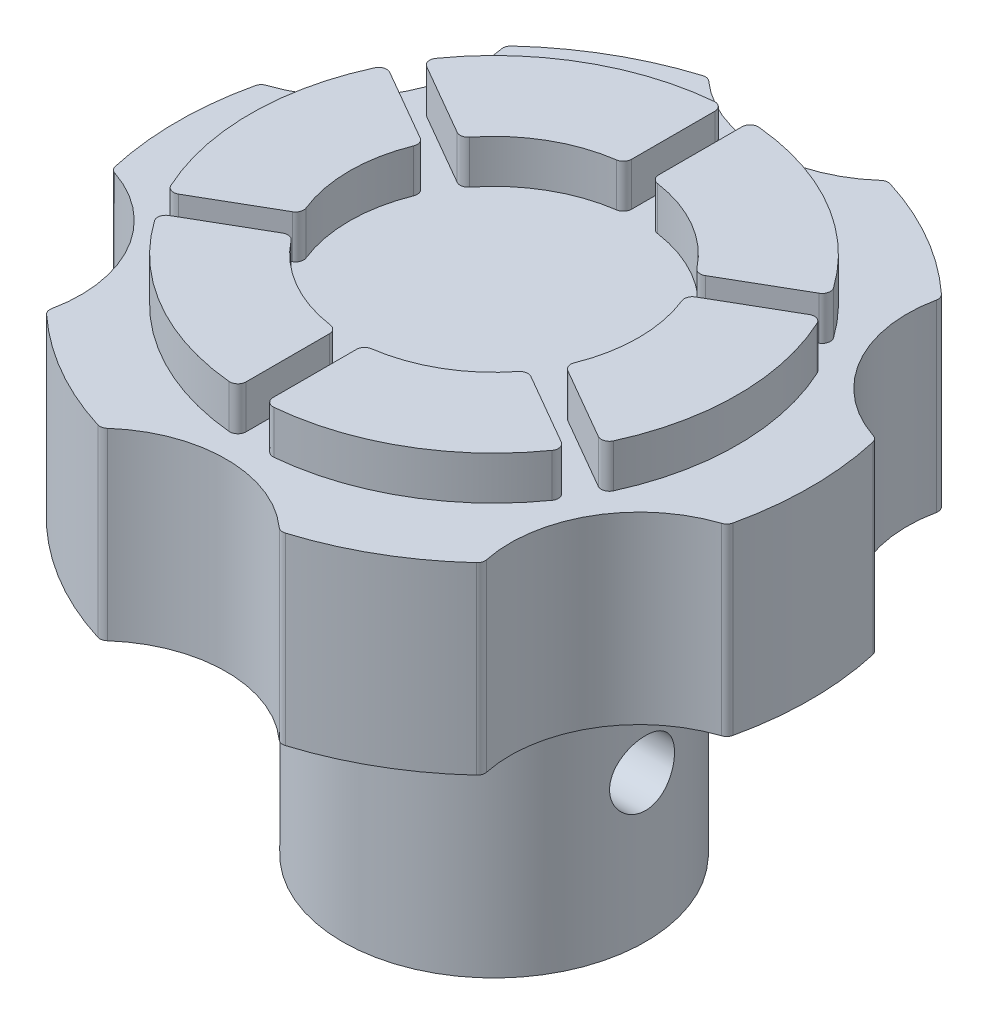
SolidWorks part; units mm, degrees
ref_plane "Alzado" through (0, 0, 0) normal (0, 0, 1) x (1, 0, 0)
ref_plane "Planta" through (0, 0, 0) normal (0, 1, 0) x (1, 0, 0)
ref_plane "Vista lateral" through (0, 0, 0) normal (1, 0, 0) x (0, 0, -1)
sketch "Croquis1" plane through (0, 0, 0) normal (0, 1, 0) x (1, 0, 0)
  line L0 (0, 0) -> (0, 24.75) construction
  line L1 (0, 24.75) -> (0, 28.0624) construction
  line L2 (-8.25, 28.0624) -> (8.25, 28.0624) construction
  line L3 (0, 0) -> (21.4341, 12.375) construction
  arc A0 (8.25, -28.0624) -> (20.1778, -21.1759) centre (0, 0) ccw
  arc A2 (-8.25, 28.0624) -> (8.25, 28.0624) centre (0, 36.68) ccw
  arc A3 (20.1778, 21.1759) -> (28.4278, 6.8865) centre (31.7658, 18.34) ccw
  arc A4 (28.4278, -6.8865) -> (20.1778, -21.1759) centre (31.7658, -18.34) ccw
  arc A5 (8.25, -28.0624) -> (-8.25, -28.0624) centre (0, -36.68) ccw
  arc A6 (-20.1778, -21.1759) -> (-28.4278, -6.8865) centre (-31.7658, -18.34) ccw
  arc A7 (-28.4278, 6.8865) -> (-20.1778, 21.1759) centre (-31.7658, 18.34) ccw
  arc A8 (28.4278, -6.8865) -> (28.4278, 6.8865) centre (0, 0) ccw
  arc A9 (-20.1778, -21.1759) -> (-8.25, -28.0624) centre (0, 0) ccw
  arc A10 (-28.4278, 6.8865) -> (-28.4278, -6.8865) centre (0, 0) ccw
  arc A11 (-8.25, 28.0624) -> (-20.1778, 21.1759) centre (0, 0) ccw
  arc A12 (20.1778, 21.1759) -> (8.25, 28.0624) centre (0, 0) ccw
  point P4 (0, 28.0624)
  point P25 (0, 0)
  dimension "D1" = 16.5
  dimension "D2" = 58.5
  dimension "D4" = 60
  dimension "D5" = 6
extrude "Saliente-Extruir1" add sketch "Croquis1" along normal blind 17
sketch "Croquis2" plane through (0, 17, 0) normal (0, 1, 0) x (1, 0, 0)
  circle A0 centre (0, 0) radius 13.35
  circle A1 centre (0, 0) radius 22.5
extrude "Saliente-Extruir2" add sketch "Croquis2" along normal blind 4
sketch "Croquis3" plane through (0, 17, 0) normal (0, 1, 0) x (1, 0, 0)
  line L0 (0, -22.5) -> (0, 22.5) construction
  line L1 (-19.4856, -11.25) -> (19.4856, 11.25) construction
  line L2 (19.4856, -11.25) -> (-19.4856, 11.25) construction
  line L3 (-1.25, 0) -> (1.25, 0) construction
  line L4 (-1.25, -22.4653) -> (-1.25, -2.1651)
  line L5 (1.25, -22.4653) -> (1.25, -2.1651)
  line L6 (-0.625, -1.0825) -> (0.625, 1.0825) construction
  line L7 (-20.0805, 10.1501) -> (-2.5, 0)
  line L8 (-18.8305, 12.3152) -> (-1.25, 2.1651)
  line L9 (-0.625, 1.0825) -> (0.625, -1.0825) construction
  line L10 (-20.0805, -10.1501) -> (-2.5, 0)
  line L11 (-18.8305, -12.3152) -> (-1.25, -2.1651)
  line L12 (1.25, 2.1651) -> (1.25, 22.4653)
  line L13 (-1.25, 2.1651) -> (-1.25, 22.4653)
  line L14 (1.25, -2.1651) -> (18.8305, -12.3152)
  line L15 (2.5, 0) -> (20.0805, 10.1501)
  line L16 (1.25, 2.1651) -> (18.8305, 12.3152)
  line L18 (2.5, 0) -> (20.0805, -10.1501)
  arc A0 (-20.0805, -10.1501) -> (-18.8305, -12.3152) centre (0, 0) ccw
  arc A1 (-18.8305, 12.3152) -> (-20.0805, 10.1501) centre (0, 0) ccw
  arc A2 (-1.25, -22.4653) -> (1.25, -22.4653) centre (0, 0) ccw
  arc A3 (18.8305, -12.3152) -> (20.0805, -10.1501) centre (0, 0) ccw
  arc A4 (20.0805, 10.1501) -> (18.8305, 12.3152) centre (0, 0) ccw
  arc A5 (1.25, 22.4653) -> (-1.25, 22.4653) centre (0, 0) ccw
  point P6 (0, 0)
  point P12 (0, 0)
  point P19 (0, 0)
  point P25 (0, 0)
  dimension "D1" = 60
  dimension "D2" = 60
  dimension "D3" = 2.5
  dimension "D4" = 2.5
  dimension "D5" = 60
  dimension "D6" = 60
  dimension "D7" = 2.5
extrude "Cortar-Extruir1" cut sketch "Croquis3" along direction (0, 1, 0) on the side of the normal blind 4
sketch "Croquis4" plane through (0, 0, 0) normal (0, -1, 0) x (1, 0, 0)
  circle A0 centre (0, 0) radius 14
  dimension "D1" = 28
extrude "Saliente-Extruir3" add sketch "Croquis4" along normal blind 2
sketch "Croquis5" plane through (0, -2, 0) normal (0, -1, 0) x (1, 0, 0)
  circle A0 centre (0, 0) radius 14
  circle A1 centre (0, 0) radius 7.9375
  dimension "D1" = 28
extrude "Saliente-Extruir4" add sketch "Croquis5" along normal blind 25
sketch "Croquis6" plane through (0, 0, 0) normal (1, 0, 0) x (0, 0, -1)
  line L0 (0, -27) -> (0, 0) construction
  line L1 (-14, -27) -> (14, -27) construction
  line L2 (-14, -13.5) -> (14, -13.5) construction
  line L3 (-14, 0) -> (-14, -27) construction
  line L4 (14, -27) -> (14, 0) construction
  circle A0 centre (0, -13.5) radius 3
  dimension "D1" = 6
extrude "Cortar-Extruir2" cut sketch "Croquis6" against normal through all both and the other way through all
fillet "Redondeo1" radius 1 1 edges at (0, 0, -14)
chamfer "Chaflán1" distance 1 angle 45 1 edges at (0, -27, -7.9375)
fillet "Redondeo2" radius 0.75 36 edges at (-28.4278, 8.5, 6.8865) (-20.1778, 8.5, 21.1759) (-8.25, 8.5, 28.0624) (8.25, 8.5, 28.0624) (20.1778, 8.5, 21.1759) (28.4278, 8.5, 6.8865) (20.1778, 8.5, -21.1759) (28.4278, 8.5, -6.8865) (8.25, 8.5, -28.0624) (-8.25, 8.5, -28.0624) (-28.4278, 8.5, -6.8865) (-20.1778, 8.5, -21.1759) (1.25, 19, -13.2914) (1.25, 19, -22.4653) (1.25, 19, 13.2914) (1.25, 19, 22.4653) (12.1356, 19, 5.5631) (12.1356, 19, -5.5631) (-18.8305, 19, 12.3152) (-10.8856, 19, 7.7282) (-1.25, 19, 13.2914) (-1.25, 19, 22.4653) (10.8856, 19, 7.7282) (20.0805, 19, 10.1501) (18.8305, 19, 12.3152) (20.0805, 19, -10.1501) (18.8305, 19, -12.3152) (10.8856, 19, -7.7282) (-20.0805, 19, 10.1501) (-12.1356, 19, 5.5631) (-1.25, 19, -13.2914) (-1.25, 19, -22.4653) (-10.8856, 19, -7.7282) (-12.1356, 19, -5.5631) (-20.0805, 19, -10.1501) (-18.8305, 19, -12.3152)
